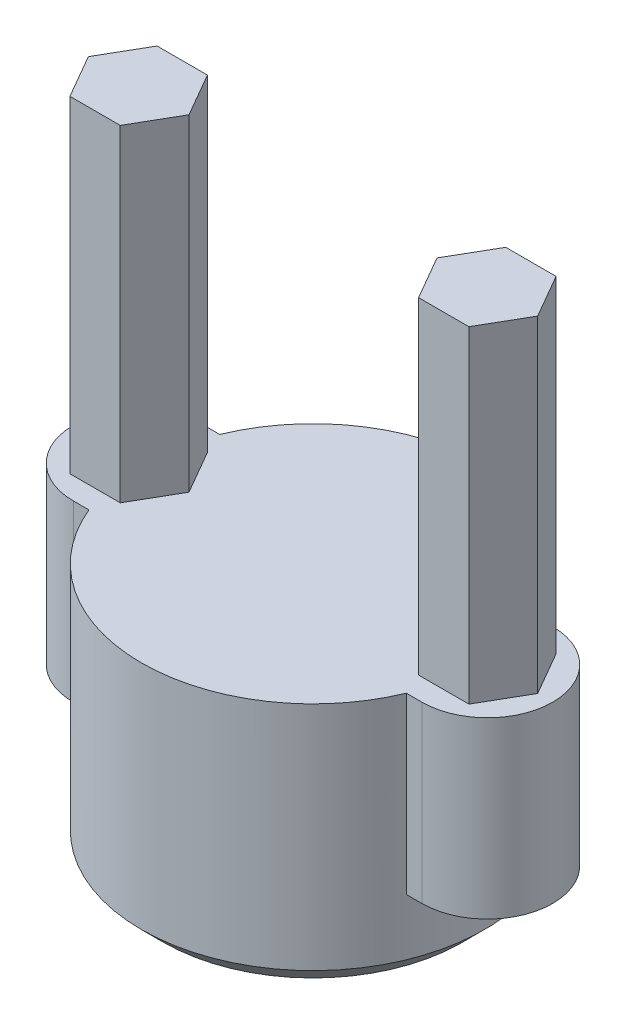
SolidWorks part; units mm, degrees
ref_plane "Front Plane" through (0, 0, 0) normal (0, 0, 1) x (1, 0, 0)
ref_plane "Top Plane" through (0, 0, 0) normal (0, 1, 0) x (1, 0, 0)
ref_plane "Right Plane" through (0, 0, 0) normal (1, 0, 0) x (0, 0, -1)
sketch "Sketch1" plane through (0, 0, 0) normal (0, 1, 0) x (1, 0, 0)
  circle A0 centre (0, 0) radius 7.875
  dimension "D1" = 15.75
extrude "Boss-Extrude1" add sketch "Sketch1" against normal blind 11.6
sketch "Sketch2" plane through (0, 0, 0) normal (0, 1, 0) x (1, 0, 0)
  line L0 (0, -1000) -> (0, 49000) construction
  line L1 (-1000, 0) -> (49000, 0) construction
  line L2 (-8, -1000) -> (-8, 49000) construction
  line L3 (-8, 3) -> (-7.2812, 3)
  line L4 (-8, -3) -> (-7.2812, -3)
  line L5 (8, -3) -> (7.2812, -3)
  line L6 (8, 3) -> (7.2812, 3)
  arc A0 (-8, 3) -> (-8, -3) centre (-8, 0) ccw
  arc A3 (-7.2812, 3) -> (-7.2812, -3) centre (0, 0) ccw
  circle A4 centre (0, 0) radius 7.875 construction
  arc A5 (7.2812, 3) -> (7.2812, -3) centre (0, 0) cw
  arc A6 (8, 3) -> (8, -3) centre (8, 0) cw
  dimension "D1" = 6
  dimension "D2" = 22
extrude "Boss-Extrude2" add sketch "Sketch2" against normal blind 8
sketch "Sketch3" plane through (0, 0, 0) normal (0, 1, 0) x (1, 0, 0)
  line L0 (-1000, 0) -> (49000, 0) construction
  line L1 (0, -1000) -> (0, 49000) construction
  line L2 (6.8453, -2) -> (5.6906, 0)
  line L3 (-5.6906, 0) -> (-6.8453, 2)
  line L4 (-6.8453, 2) -> (-9.1547, 2)
  line L5 (-9.1547, 2) -> (-10.3094, 0)
  line L6 (-10.3094, 0) -> (-9.1547, -2)
  line L7 (-9.1547, -2) -> (-6.8453, -2)
  line L8 (-6.8453, -2) -> (-5.6906, 0)
  line L9 (9.1547, -2) -> (6.8453, -2)
  line L10 (10.3094, 0) -> (9.1547, -2)
  line L11 (9.1547, 2) -> (10.3094, 0)
  line L12 (6.8453, 2) -> (9.1547, 2)
  line L13 (5.6906, 0) -> (6.8453, 2)
  circle A0 centre (-8, 0) radius 2 construction
  arc A1 (-8, 3) -> (-8, -3) centre (-8, 0) ccw construction
  circle A2 centre (8, 0) radius 2 construction
  point P6 (-8, 2)
  dimension "D1" = 4
extrude "Boss-Extrude3" add sketch "Sketch3" along normal blind 15
sketch "Sketch4" plane through (0, 0, 0) normal (0, 0, 1) x (1, 0, 0)
  line L0 (0, -1000) -> (0, 49000) construction
  line L1 (0, -15) -> (8.4125, -15) construction
  line L2 (-7.875, -11.6) -> (7.875, -11.6) construction
  line L3 (0, -11.6) -> (5.15, -11.6)
  line L4 (0, -15) -> (0, -11.6)
  arc A0 (0, -15) -> (5.15, -11.6) centre (0, -9.3996) ccw
  dimension "D2" = 10.3
  dimension "D1" = 15
revolve "Revolve1" add sketch "Sketch4" angle 360 about L4
chamfer "Chamfer1" distance 1 angle 45 1 edges at (0, -11.6, 7.875)
